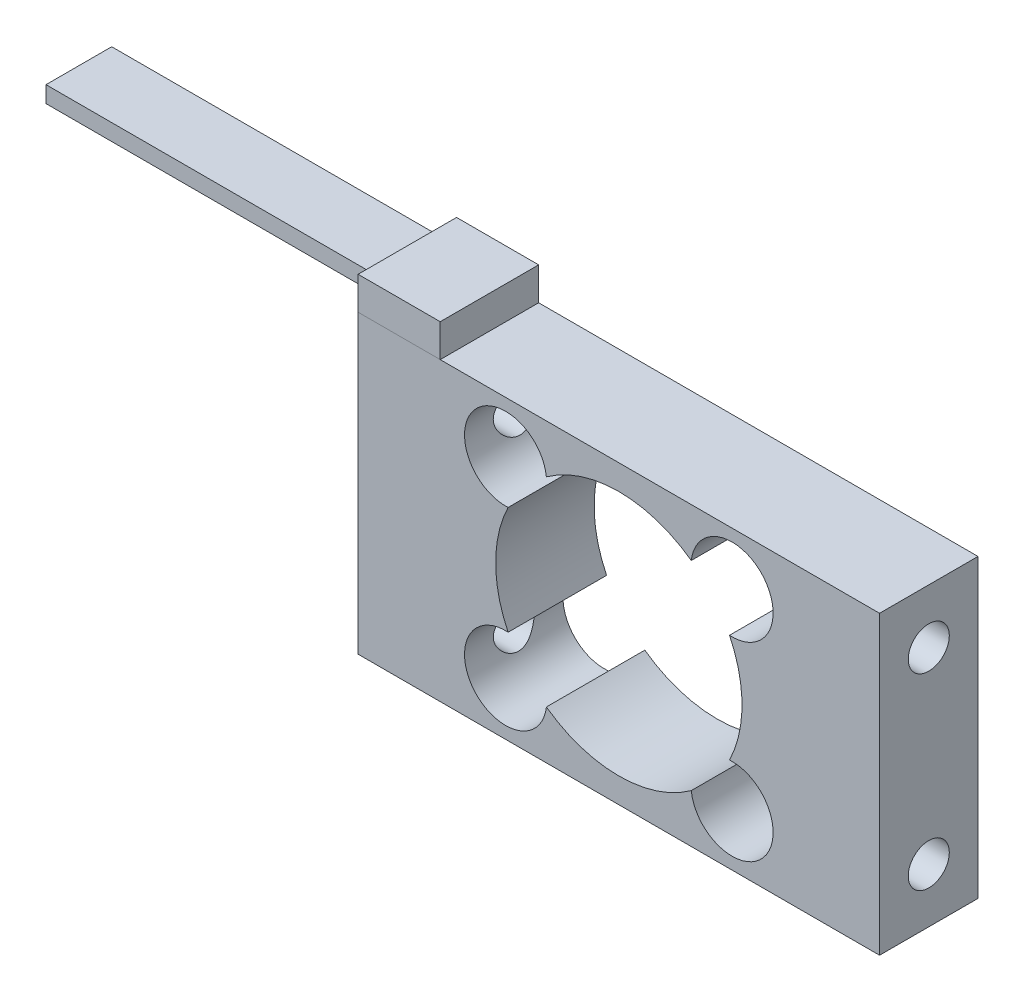
SolidWorks part; units mm, degrees
material "AISI 316 Annealed Stainless Steel Bar (SS)"
ref_plane "Front Plane" through (0, 0, 0) normal (0, 0, 1) x (1, 0, 0)
ref_plane "Top Plane" through (0, 0, 0) normal (0, 1, 0) x (1, 0, 0)
ref_plane "Right Plane" through (0, 0, 0) normal (1, 0, 0) x (0, 0, -1)
sketch "Sketch1" plane through (0, 0, 0) normal (0, 0, 1) x (1, 0, 0)
  line L1 (15.875, -9.017) -> (-15.875, -9.017)
  line L2 (15.875, -9.017) -> (15.875, 9.017)
  line L3 (15.875, 9.017) -> (-15.875, 9.017)
  line L4 (-15.875, -9.017) -> (-15.875, 9.017)
  line L5 (15.875, -9.017) -> (-15.875, 9.017) construction
  line L6 (15.875, 9.017) -> (-15.875, -9.017) construction
  point P0 (0, 0)
  dimension "D1" = 31.75
  dimension "D2" = 18.034
extrude "Boss-Extrude1" add sketch "Sketch1" along normal mid plane 5.9944
hole_wizard "M3 Tapped Hole1" positions "Sketch2" profile "Sketch3" tap size "M3" standard "ISO"
sketch "Sketch2" plane through (15.875, 0, 0) normal (1, 0, 0) x (0, 0, -1)
  line L0 (0, -5.715) -> (0, 5.715) construction
  point P0 (0, 5.715)
  point P2 (0, -5.715)
  dimension "D1" = 11.43
sketch "Sketch3" plane through (15.875, 5.715, 0) normal (0, 1, 0) x (0, 0, -1)
  line L0 (0, 0) -> (0, 9.2511)
  line L1 (0, 9.2511) -> (1.25, 8.5)
  line L2 (1.25, 8.5) -> (1.25, 0)
  line L5 (1.25, 0) -> (0, 0)
  line L10 (0, 9.2511) -> (-1.25, 8.5) construction
  line L11 (0, -6.35) -> (0, 107.95) construction
  dimension "Tap Drill Dia." = 2.5
  dimension "Tap Drill Depth" = 8.5
  dimension "Drill Angle" = 118
cosmetic thread "Hole Thread1" parameters "D1"=6, "D2"=3
cosmetic thread "Hole Thread2" parameters "D1"=6, "D2"=3
mirror "Mirror1" about plane through (0, 0, 0) normal (1, 0, 0) of "M3 Tapped Hole1"
sketch "Sketch4" plane through (0, 0, 0) normal (0, 0, 1) x (1, 0, 0)
  circle A0 centre (0, 0) radius 7.5
  dimension "D1" = 15
extrude "Cut-Extrude1" cut sketch "Sketch4" against normal through all both and the other way through all
sketch "Sketch5" plane through (0, 0, 0) normal (0, 0, 1) x (1, 0, 0)
  line L0 (0, 0) -> (-6.8944, 5.7851) construction
  line L1 (0, -1000) -> (0, 49000) construction
  circle A0 centre (-6.8944, 5.7851) radius 2.5
  dimension "D1" = 50
  dimension "D3" = 5
  dimension "D2" = 9
extrude "Cut-Extrude2" cut sketch "Sketch5" against normal through all both and the other way through all
mirror "Mirror2" about plane through (0, 0, 0) normal (0, 1, 0) of "Cut-Extrude2"
mirror "Mirror3" about plane through (0, 0, 0) normal (1, 0, 0) of "Cut-Extrude2", "Mirror2"
sketch "Sketch6" plane through (0, 9.017, 0) normal (0, 1, 0) x (1, 0, 0)
  line L0 (15.875, 2.9972) -> (-15.875, 2.9972) construction
  line L1 (-15.875, -2.9972) -> (-10.875, -2.9972)
  line L2 (-15.875, -2.9972) -> (-15.875, 2.9972)
  line L3 (-15.875, 2.9972) -> (-10.875, 2.9972)
  line L4 (-10.875, -2.9972) -> (-10.875, 2.9972)
  line L5 (-15.875, -2.9972) -> (-10.875, 2.9972) construction
  line L6 (-15.875, 2.9972) -> (-10.875, -2.9972) construction
  point P4 (-13.375, 0)
  dimension "D1" = 5
extrude "Boss-Extrude2" add sketch "Sketch6" along normal blind 2 separate body
sketch "Sketch7" plane through (-15.875, 0, 0) normal (-1, 0, 0) x (0, 0, 1)
  line L0 (0, 11.017) -> (0, 9.017) construction
  line L1 (2, 10.517) -> (-2, 10.517)
  line L2 (2, 10.517) -> (2, 9.517)
  line L3 (2, 9.517) -> (-2, 9.517)
  line L4 (-2, 10.517) -> (-2, 9.517)
  line L5 (2, 10.517) -> (-2, 9.517) construction
  line L6 (2, 9.517) -> (-2, 10.517) construction
  line L7 (-2.9972, 11.017) -> (2.9972, 11.017) construction
  line L8 (2.9972, 9.017) -> (-2.9972, 9.017) construction
  point P0 (0, 10.017)
  dimension "D1" = 1
  dimension "D2" = 4
extrude "Boss-Extrude3" add sketch "Sketch7" along normal blind 20
sketch "Sketch8" plane through (0, -9.017, 0) normal (0, -1, 0) x (1, 0, 0)
  line L0 (-15.875, 2.9972) -> (15.875, 2.9972) construction
  line L1 (15.875, -2.9972) -> (10.875, -2.9972)
  line L2 (15.875, -2.9972) -> (15.875, 2.9972)
  line L3 (15.875, 2.9972) -> (10.875, 2.9972)
  line L4 (10.875, -2.9972) -> (10.875, 2.9972)
  line L5 (15.875, -2.9972) -> (10.875, 2.9972) construction
  line L6 (15.875, 2.9972) -> (10.875, -2.9972) construction
  point P4 (13.375, 0)
  dimension "D1" = 5
extrude "Boss-Extrude4" [suppressed] add sketch "Sketch8" along normal blind 2 separate body
sketch "Sketch9" [suppressed] plane through (15.875, 0, 0) normal (1, 0, 0) x (0, 0, -1)
  line L0 (0, -9.017) -> (0, -11.017) construction
  line L1 (2, -10.517) -> (-2, -10.517)
  line L2 (2, -10.517) -> (2, -9.517)
  line L3 (2, -9.517) -> (-2, -9.517)
  line L4 (-2, -10.517) -> (-2, -9.517)
  line L5 (2, -10.517) -> (-2, -9.517) construction
  line L6 (2, -9.517) -> (-2, -10.517) construction
  line L7 (2.9972, -9.017) -> (-2.9972, -9.017) construction
  line L8 (2.9972, -11.017) -> (-2.9972, -11.017) construction
  point P0 (0, -10.017)
  dimension "D1" = 4
  dimension "D2" = 1
extrude "Boss-Extrude5" [suppressed] add sketch "Sketch9" along normal blind 20 separate body
sketch "Sketch10" plane through (0, -9.017, 0) normal (0, -1, 0) x (1, 0, 0)
  line L0 (-15.875, -2.9972) -> (15.875, -2.9972) construction
  line L1 (-15.875, 2.9972) -> (-10.875, 2.9972)
  line L2 (-15.875, 2.9972) -> (-15.875, -2.9972)
  line L3 (-15.875, -2.9972) -> (-10.875, -2.9972)
  line L4 (-10.875, 2.9972) -> (-10.875, -2.9972)
  line L5 (-15.875, 2.9972) -> (-10.875, -2.9972) construction
  line L6 (-15.875, -2.9972) -> (-10.875, 2.9972) construction
  point P4 (-13.375, 0)
  dimension "D1" = 5
extrude "Boss-Extrude6" [suppressed] add sketch "Sketch10" along normal blind 2 separate body
sketch "Sketch11" [suppressed] plane through (-15.875, 0, 0) normal (-1, 0, 0) x (0, 0, 1)
  line L0 (0, -9.017) -> (0, -11.017) construction
  line L1 (2, -10.517) -> (-2, -10.517)
  line L2 (2, -10.517) -> (2, -9.517)
  line L3 (2, -9.517) -> (-2, -9.517)
  line L4 (-2, -10.517) -> (-2, -9.517)
  line L5 (2, -10.517) -> (-2, -9.517) construction
  line L6 (2, -9.517) -> (-2, -10.517) construction
  line L7 (2.9972, -9.017) -> (-2.9972, -9.017) construction
  line L8 (2.9972, -11.017) -> (-2.9972, -11.017) construction
  point P0 (0, -10.017)
  dimension "D1" = 1
  dimension "D2" = 4
extrude "Boss-Extrude7" [suppressed] add sketch "Sketch11" along normal blind 20 separate body
